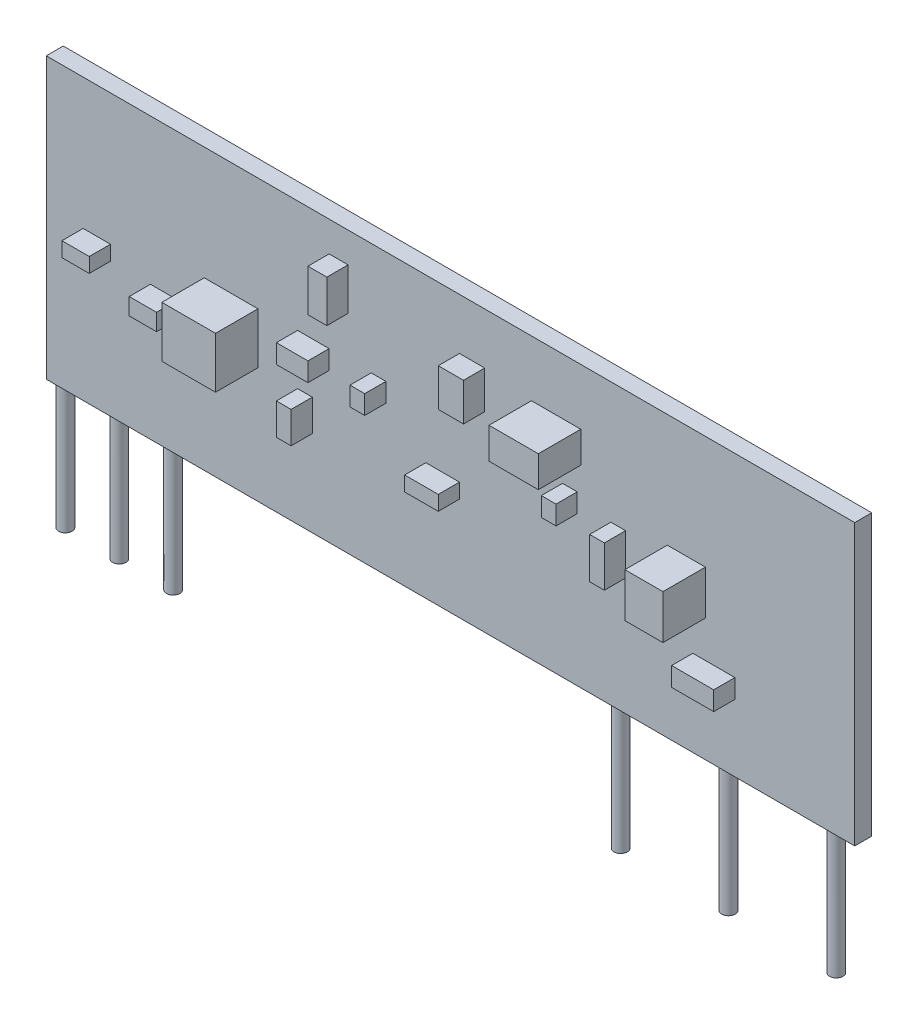
SolidWorks part; units mm, degrees
ref_plane "Plan de face" through (0, 0, 0) normal (0, 0, 1) x (1, 0, 0)
ref_plane "Plan de dessus" through (0, 0, 0) normal (0, 1, 0) x (1, 0, 0)
ref_plane "Plan de droite" through (0, 0, 0) normal (1, 0, 0) x (0, 0, -1)
sketch "Esquisse1" plane through (0, 0, 0) normal (0, 0, 1) x (1, 0, 0)
  line L1 (0, 0) -> (38.1, 0)
  line L2 (0, 0) -> (0, 13.2)
  line L3 (0, 13.2) -> (38.1, 13.2)
  line L4 (38.1, 0) -> (38.1, 13.2)
  dimension "D1" = 38.1
  dimension "D2" = 13.2
extrude "Boss.-Extru.1" add sketch "Esquisse1" along normal blind 0.8
sketch "Esquisse2" plane through (0, 0, 0) normal (0, -1, 0) x (1, 0, 0)
  line L0 (0, 0.8) -> (0, 0) construction
  line L1 (38.1, 0.8) -> (38.1, 0) construction
  circle A0 centre (0.5, 0.3997) radius 0.315
  circle A1 centre (3.04, 0.3997) radius 0.315
  circle A2 centre (5.58, 0.3997) radius 0.315
  circle A3 centre (26.67, 0.3997) radius 0.315
  circle A4 centre (31.75, 0.3997) radius 0.315
  circle A5 centre (36.83, 0.3997) radius 0.315
  dimension "D1" = 0.63
  dimension "D4" = 0.63
  dimension "D6" = 0.63
  dimension "D7" = 0.63
  dimension "D8" = 0.63
  dimension "D9" = 0.63
  dimension "D2" = 0.5
  dimension "D3" = 2.54
  dimension "D5" = 2.54
  dimension "D10" = 5.08
  dimension "D11" = 1.27
  dimension "D12" = 5.08
extrude "Boss.-Extru.2" add sketch "Esquisse2" along normal blind 6
sketch "Esquisse3" plane through (0, 0, 0.8) normal (0, 0, 1) x (1, 0, 0)
  line L1 (7.4461, 7.8622) -> (9.9749, 7.8622)
  line L2 (7.4461, 7.8622) -> (7.4461, 5.4558)
  line L3 (7.4461, 5.4558) -> (9.9749, 5.4558)
  line L4 (9.9749, 7.8622) -> (9.9749, 5.4558)
  line L5 (22.8636, 10.5542) -> (25.1884, 10.5542)
  line L6 (22.8636, 10.5542) -> (22.8636, 9.0858)
  line L7 (22.8636, 9.0858) -> (25.1884, 9.0858)
  line L8 (25.1884, 10.5542) -> (25.1884, 9.0858)
  line L9 (29.2671, 7.8622) -> (31.0617, 7.8622)
  line L10 (29.2671, 7.8622) -> (29.2671, 5.7821)
  line L11 (29.2671, 5.7821) -> (31.0617, 5.7821)
  line L12 (31.0617, 7.8622) -> (31.0617, 5.7821)
extrude "Boss.-Extru.3" add sketch "Esquisse3" along normal blind 2
sketch "Esquisse4" plane through (0, 0, 0.8) normal (0, 0, 1) x (1, 0, 0)
  line L1 (4.9084, 6.3298) -> (6.1964, 6.3298)
  line L2 (4.9084, 6.3298) -> (4.9084, 5.5372)
  line L3 (4.9084, 5.5372) -> (6.1964, 5.5372)
  line L4 (6.1964, 6.3298) -> (6.1964, 5.5372)
  line L5 (1.7379, 7.0234) -> (3.0259, 7.0234)
  line L6 (1.7379, 7.0234) -> (1.7379, 6.3298)
  line L7 (1.7379, 6.3298) -> (3.0259, 6.3298)
  line L8 (3.0259, 7.0234) -> (3.0259, 6.3298)
  line L9 (11.844, 5.5372) -> (12.5375, 5.5372)
  line L10 (11.844, 5.5372) -> (11.844, 4.051)
  line L11 (11.844, 4.051) -> (12.5375, 4.051)
  line L12 (12.5375, 5.5372) -> (12.5375, 4.051)
  line L13 (11.844, 7.9151) -> (13.3301, 7.9151)
  line L14 (11.844, 7.9151) -> (11.844, 7.0234)
  line L15 (11.844, 7.0234) -> (13.3301, 7.0234)
  line L16 (13.3301, 7.9151) -> (13.3301, 7.0234)
  line L17 (17.8878, 5.5372) -> (19.4731, 5.5372)
  line L18 (17.8878, 5.5372) -> (17.8878, 4.8436)
  line L19 (17.8878, 4.8436) -> (19.4731, 4.8436)
  line L20 (19.4731, 5.5372) -> (19.4731, 4.8436)
  line L21 (15.3117, 7.9151) -> (16.0053, 7.9151)
  line L22 (15.3117, 7.9151) -> (15.3117, 7.0234)
  line L23 (15.3117, 7.0234) -> (16.0053, 7.0234)
  line L24 (16.0053, 7.9151) -> (16.0053, 7.0234)
  line L25 (13.3301, 11.7792) -> (14.2219, 11.7792)
  line L26 (13.3301, 11.7792) -> (13.3301, 9.7976)
  line L27 (13.3301, 9.7976) -> (14.2219, 9.7976)
  line L28 (14.2219, 11.7792) -> (14.2219, 9.7976)
  line L29 (19.4731, 10.7884) -> (20.662, 10.7884)
  line L30 (19.4731, 10.7884) -> (19.4731, 9.0049)
  line L31 (19.4731, 9.0049) -> (20.662, 9.0049)
  line L32 (20.662, 10.7884) -> (20.662, 9.0049)
  line L33 (24.3279, 7.9151) -> (25.0215, 7.9151)
  line L34 (24.3279, 7.9151) -> (24.3279, 7.0234)
  line L35 (24.3279, 7.0234) -> (25.0215, 7.0234)
  line L36 (25.0215, 7.9151) -> (25.0215, 7.0234)
  line L37 (26.6068, 7.4692) -> (27.3003, 7.4692)
  line L38 (26.6068, 7.4692) -> (26.6068, 5.5372)
  line L39 (26.6068, 5.5372) -> (27.3003, 5.5372)
  line L40 (27.3003, 7.4692) -> (27.3003, 5.5372)
  line L41 (30.4709, 4.051) -> (32.4524, 4.051)
  line L42 (30.4709, 4.051) -> (30.4709, 3.1593)
  line L43 (30.4709, 3.1593) -> (32.4524, 3.1593)
  line L44 (32.4524, 4.051) -> (32.4524, 3.1593)
extrude "Boss.-Extru.8" add sketch "Esquisse4" along normal blind 1
